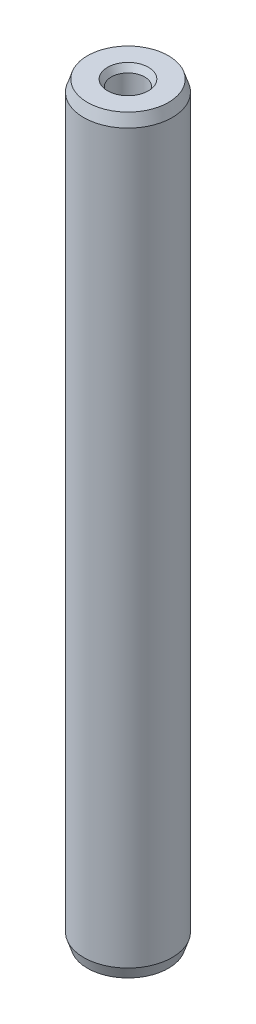
SolidWorks part; units mm, degrees
ref_plane "Front Plane" through (0, 0, 0) normal (0, 0, 1) x (1, 0, 0)
ref_plane "Top Plane" through (0, 0, 0) normal (0, 1, 0) x (1, 0, 0)
ref_plane "Right Plane" through (0, 0, 0) normal (1, 0, 0) x (0, 0, -1)
ref_plane "Plane1" through (0, 0, -1.1264) normal (0, 0, -1) x (-1, 0, 0)
sketch "Sketch1" plane through (0, 0, -1.1264) normal (0, 0, -1) x (-1, 0, 0)
  line L0 (-0.0644, -17.1991) -> (1.0659, -16.5199)
  line L1 (1.0659, -16.5199) -> (1.0659, 21.4918)
  line L2 (1.0659, 21.4918) -> (-0.0644, 22.1709)
  line L3 (-0.0644, 22.1709) -> (-0.0644, 27.446)
  line L4 (-0.0644, 27.446) -> (-0.3184, 27.8859)
  line L5 (-0.3184, 27.8859) -> (-1.6773, 27.8859)
  line L6 (-1.6773, 27.8859) -> (-1.9313, 27.1239)
  line L7 (-1.9313, 27.1239) -> (-1.9313, -22.1521)
  line L8 (-1.9313, -22.1521) -> (-1.6773, -22.9141)
  line L9 (-1.6773, -22.9141) -> (-0.3184, -22.9141)
  line L10 (-0.3184, -22.9141) -> (-0.0644, -22.4741)
  line L11 (-0.0644, -22.4741) -> (-0.0644, -17.1991)
  line L12 (1.0659, -22.9141) -> (1.0659, 27.8859) construction
revolve "Revolve1" add sketch "Sketch1" angle 360 about L12
